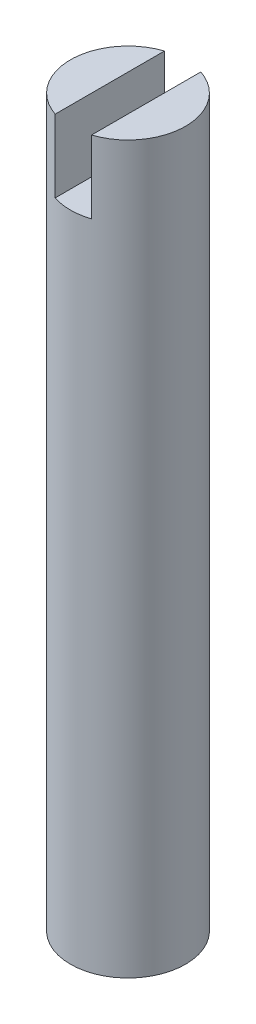
SolidWorks part; units mm, degrees
ref_plane "Front Plane" through (0, 0, 0) normal (0, 0, 1) x (1, 0, 0)
ref_plane "Top Plane" through (0, 0, 0) normal (0, 1, 0) x (1, 0, 0)
ref_plane "Right Plane" through (0, 0, 0) normal (1, 0, 0) x (0, 0, -1)
sketch "Sketch1" plane through (0, 0, 0) normal (0, 1, 0) x (1, 0, 0)
  circle A0 centre (0, 0) radius 1.587
extrude "Boss-Extrude1" add sketch "Sketch1" along normal blind 20
sketch "Sketch2" plane through (0, 20, 0) normal (0, 1, 0) x (1, 0, 0)
  line L0 (0, 0) -> (0, 1.587) construction
  line L1 (0, 1.587) -> (-0.5, 1.587)
  line L2 (0, 0) -> (0, -1.587) construction
  line L3 (0, -1.587) -> (0.5, -1.587)
  line L5 (-0.5, 1.587) -> (0.5, 1.587)
  line L6 (-0.5, 1.587) -> (-0.5, -1.587)
  line L7 (-0.5, -1.587) -> (0.5, -1.587)
  line L8 (0.5, 1.587) -> (0.5, -1.587)
  circle A0 centre (0, 0) radius 1.587 construction
  circle M5 centre (0, 0) radius 1.587
extrude "Cut-Extrude1" cut sketch "Sketch2" against normal blind 2 contours L8 L6 M5
